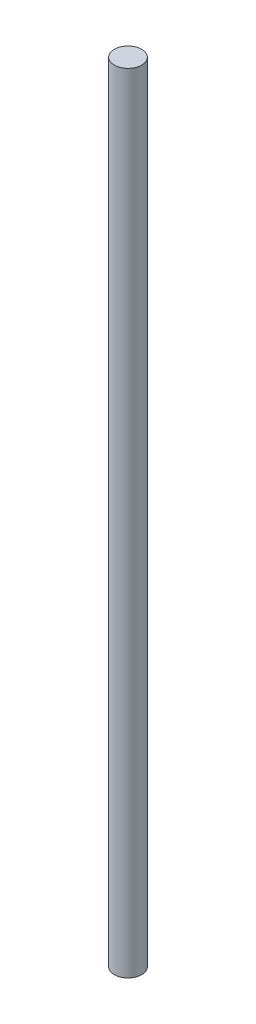
SolidWorks part; units mm, degrees
ref_plane "前视基准面" through (0, 0, 0) normal (0, 0, 1) x (1, 0, 0)
ref_plane "上视基准面" through (0, 0, 0) normal (0, 1, 0) x (1, 0, 0)
ref_plane "右视基准面" through (0, 0, 0) normal (1, 0, 0) x (0, 0, -1)
sketch "草图1" plane through (0, 0, 0) normal (0, 1, 0) x (1, 0, 0)
  circle A0 centre (0, 0) radius 4
extrude "凸台-拉伸2" add sketch "草图1" along normal blind 230
